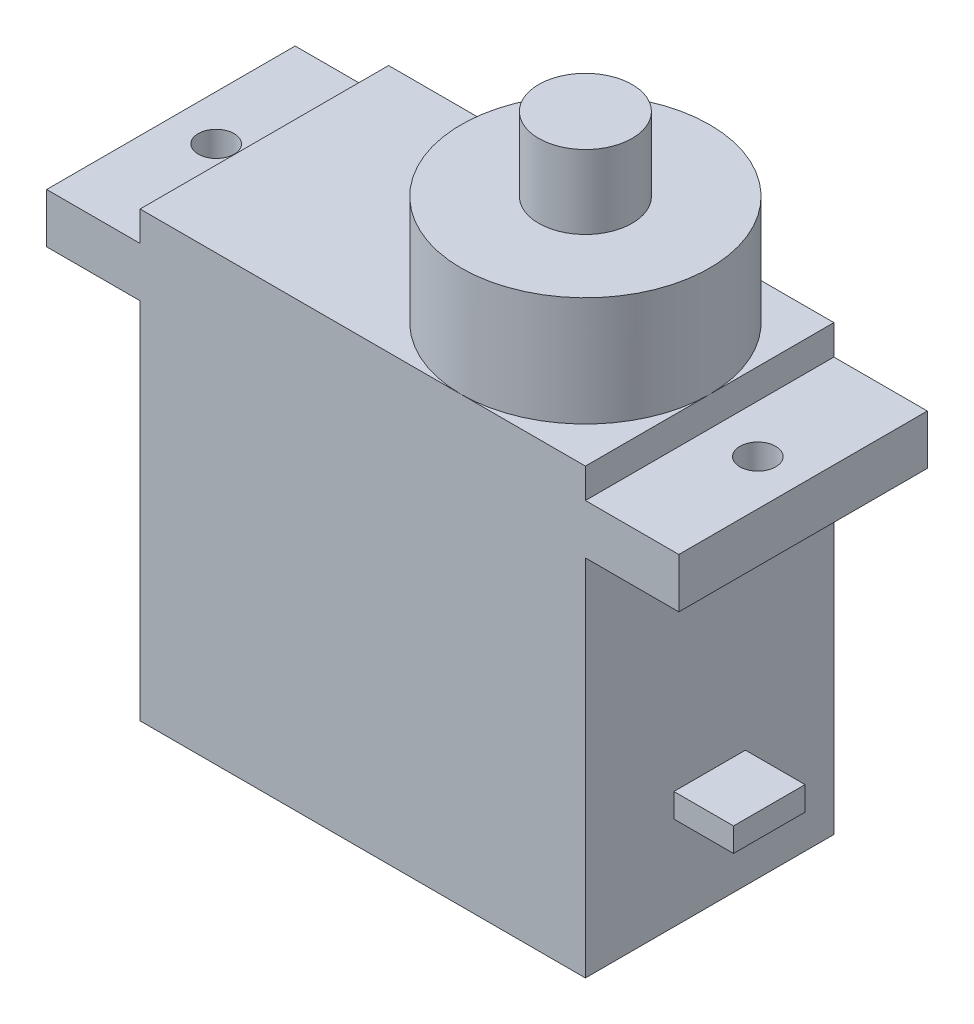
SolidWorks part; units mm, degrees
ref_plane "前视基准面" through (0, 0, 0) normal (0, 0, 1) x (1, 0, 0)
ref_plane "上视基准面" through (0, 0, 0) normal (0, 1, 0) x (1, 0, 0)
ref_plane "右视基准面" through (0, 0, 0) normal (1, 0, 0) x (0, 0, -1)
sketch "草图1" plane through (0, 0, 0) normal (0, 0, 1) x (1, 0, 0)
  line L1 (0, 0) -> (22.4, 0)
  line L2 (0, 0) -> (0, 22.3)
  line L3 (0, 22.3) -> (22.4, 22.3)
  line L4 (22.4, 0) -> (22.4, 22.3)
  dimension "D1" = 22.4
  dimension "D2" = 22.3
extrude "凸台-拉伸1" add sketch "草图1" along normal blind 12.5
sketch "草图5" plane through (0, 22.3, 0) normal (0, 1, 0) x (1, 0, 0)
  line L0 (22.4, -6.25) -> (-11.6587, -6.25) construction
  circle A0 centre (16.15, -6.25) radius 6.25
extrude "凸台-拉伸4" add sketch "草图5" along normal blind 5.5
sketch "草图6" plane through (0, 27.8, 0) normal (0, 1, 0) x (1, 0, 0)
  circle A0 centre (16.15, -6.25) radius 2.35
  dimension "D1" = 4.7
extrude "凸台-拉伸5" add sketch "草图6" along normal blind 3.7
sketch "草图10" plane through (22.4, 0, 0) normal (1, 0, 0) x (0, 0, -1)
  line L0 (-12.5, 0) -> (-12.5, 22.3) construction
  line L1 (-12.5, 18.3) -> (0, 18.3)
  line L2 (-12.5, 18.3) -> (-12.5, 20.8)
  line L3 (-12.5, 20.8) -> (0, 20.8)
  line L4 (0, 18.3) -> (0, 20.8)
  line L5 (0, 0) -> (0, 22.3) construction
  line L6 (-12.5, 0) -> (0, 0) construction
  dimension "D1" = 2.5
  dimension "D2" = 18.3
extrude "凸台-拉伸8" add sketch "草图10" along normal blind 4.7
sketch "草图11" plane through (0, 0, 0) normal (-1, 0, 0) x (0, 0, 1)
  line L0 (0, 22.3) -> (0, 0) construction
  line L1 (0, 18.3) -> (12.5, 18.3)
  line L2 (0, 18.3) -> (0, 20.8)
  line L3 (0, 20.8) -> (12.5, 20.8)
  line L4 (12.5, 18.3) -> (12.5, 20.8)
  line L5 (12.5, 22.3) -> (12.5, 0) construction
  line L6 (12.5, 0) -> (0, 0) construction
  dimension "D1" = 2.5
  dimension "D2" = 18.3
extrude "凸台-拉伸9" add sketch "草图11" along normal blind 4.7
sketch "草图12" plane through (0, 20.8, 0) normal (0, 1, 0) x (1, 0, 0)
  line L0 (-4.7, -6.25) -> (27.1, -6.25) construction
  line L1 (-4.7, -12.5) -> (-4.7, 0) construction
  line L2 (27.1, 0) -> (27.1, -12.5) construction
  line L3 (11.2, -6.25) -> (11.2, 1.6016) construction
  circle A0 centre (-2.422, -6.25) radius 0.9
  circle A1 centre (24.822, -6.25) radius 0.9
  dimension "D1" = 1.8
extrude "切除-拉伸2" cut sketch "草图12" against normal blind 4.7
sketch "草图13" plane through (22.4, 0, 0) normal (1, 0, 0) x (0, 0, -1)
  line L0 (-6.25, 0) -> (-6.25, 8.6523) construction
  line L1 (-8.05, 5.9) -> (-4.45, 5.9)
  line L2 (-8.05, 5.9) -> (-8.05, 4.7)
  line L3 (-8.05, 4.7) -> (-4.45, 4.7)
  line L4 (-4.45, 5.9) -> (-4.45, 4.7)
  line L5 (-8.05, 5.9) -> (-4.45, 4.7) construction
  line L6 (-8.05, 4.7) -> (-4.45, 5.9) construction
  line L7 (-12.5, 0) -> (0, 0) construction
  line L8 (-6.25, 8.6523) -> (-6.1132, 8.6843) construction
  line L9 (-12.5, 18.3) -> (0, 18.3) construction
  point P0 (-6.25, 5.3)
  dimension "D1" = 3.6
  dimension "D2" = 1.2
  dimension "D3" = 13
extrude "凸台-拉伸10" add sketch "草图13" along normal blind 3
